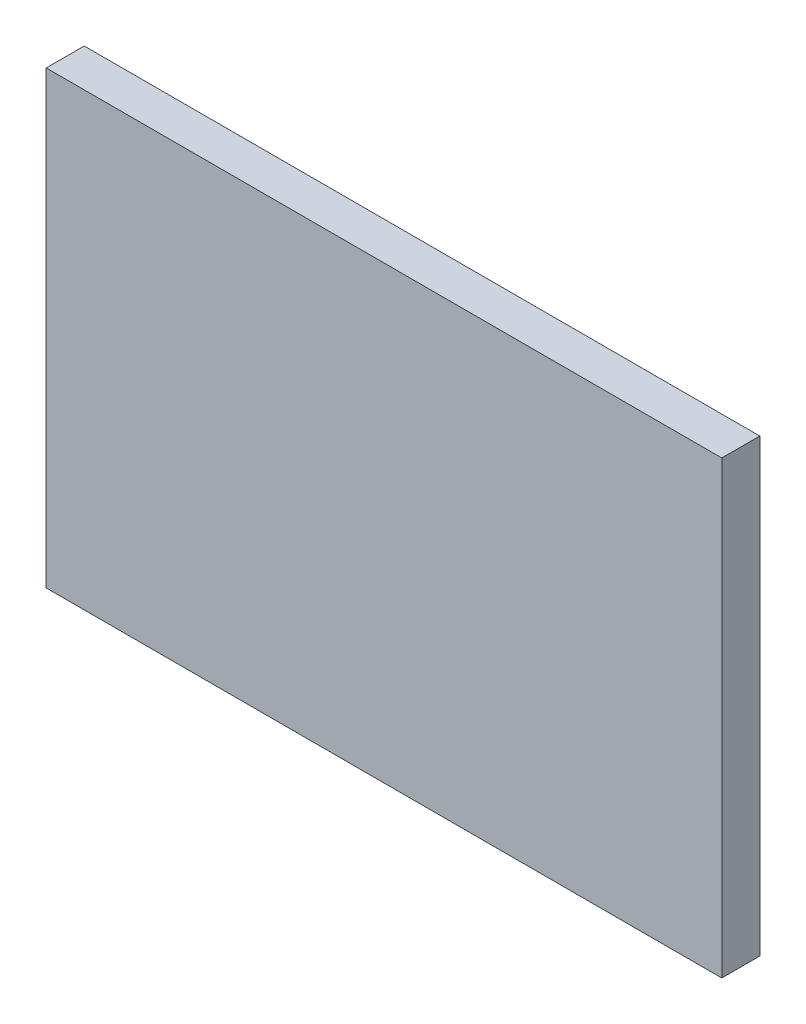
SolidWorks part; units mm, degrees
ref_plane "Front Plane" through (0, 0, 0) normal (0, 0, 1) x (1, 0, 0)
ref_plane "Top Plane" through (0, 0, 0) normal (0, 1, 0) x (1, 0, 0)
ref_plane "Right Plane" through (0, 0, 0) normal (1, 0, 0) x (0, 0, -1)
sketch "Sketch1" plane through (0, 0, 0) normal (0, 0, 1) x (1, 0, 0)
  line L1 (-159.7684, -131.3731) -> (-54.9934, -131.3731)
  line L2 (-159.7684, -131.3731) -> (-159.7684, -61.5231)
  line L3 (-159.7684, -61.5231) -> (-54.9934, -61.5231)
  line L4 (-54.9934, -131.3731) -> (-54.9934, -61.5231)
  line L5 (-159.7684, -131.3731) -> (-54.9934, -61.5231) construction
  line L6 (-159.7684, -61.5231) -> (-54.9934, -131.3731) construction
  point P0 (-107.3809, -96.4481)
  dimension "D1" = 69.85
  dimension "D2" = 104.775
extrude "Boss-Extrude1" add sketch "Sketch1" along normal blind 5.8928
